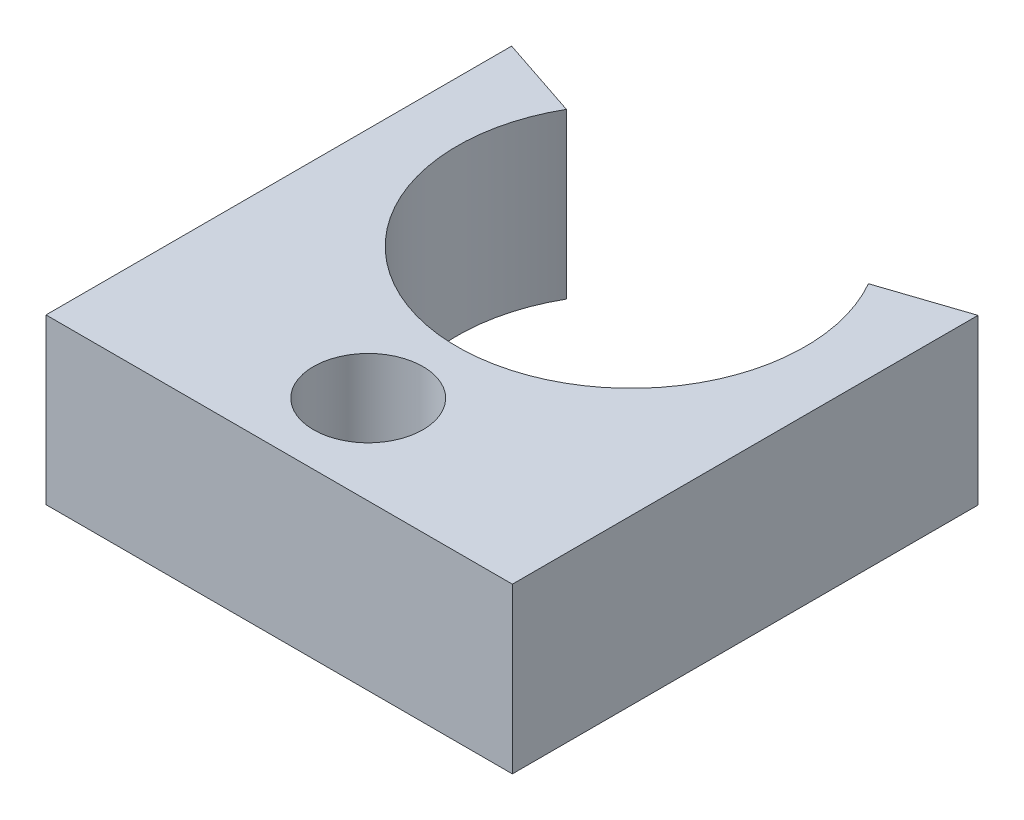
SolidWorks part; units mm, degrees
ref_plane "Front Plane" through (0, 0, 0) normal (0, 0, 1) x (1, 0, 0)
ref_plane "Top Plane" through (0, 0, 0) normal (0, 1, 0) x (1, 0, 0)
ref_plane "Right Plane" through (0, 0, 0) normal (1, 0, 0) x (0, 0, -1)
sketch "Sketch1" plane through (0, 0, 0) normal (0, 1, 0) x (1, 0, 0)
  line L0 (-34.0545, 34) -> (-34.0545, 0)
  line L1 (-34.0545, 0) -> (0, 0)
  line L2 (0, 0) -> (0, 34)
  line L3 (0, 34) -> (-6, 32)
  line L4 (-34.0545, 34) -> (-28.0545, 32)
  line L5 (-55, 0) -> (55, 0) construction
  line L6 (-17.0272, 13) -> (-17.0272, 0) construction
  arc A1 (-28.0545, 32) -> (-6, 32) centre (-17.0272, 25.7) ccw
  circle A2 centre (-17.0272, 6.5) radius 4
  point P6 (-14.6487, 2.7099)
  point P7 (0, 0)
  point P13 (-17.0272, 13)
  dimension "D2" = 6
  dimension "D3" = 6
  dimension "D1" = 12.7
  dimension "D8" = 8
  dimension "D4" = 2
  dimension "D5" = 13
  dimension "D6" = 34
  dimension "D7" = 2
extrude "Boss-Extrude1" add sketch "Sketch1" along normal blind 12
